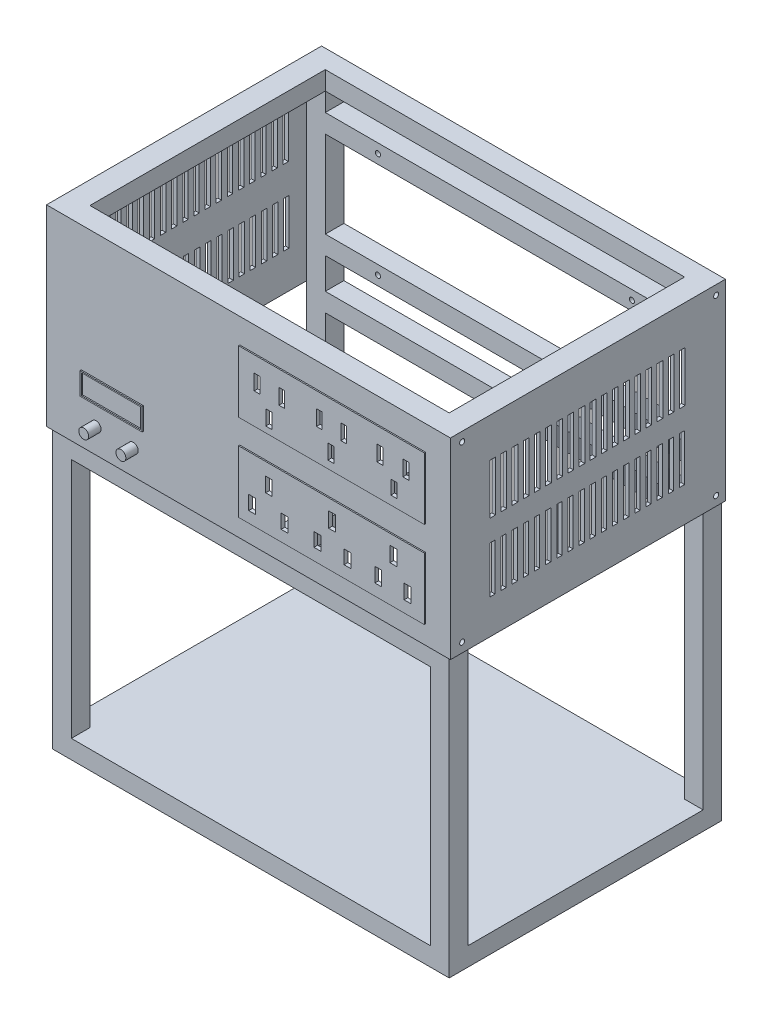
SolidWorks part; units mm, degrees
ref_plane "前视基准面" through (0, 0, 0) normal (0, 0, 1) x (1, 0, 0)
ref_plane "上视基准面" through (0, 0, 0) normal (0, 1, 0) x (1, 0, 0)
ref_plane "右视基准面" through (0, 0, 0) normal (1, 0, 0) x (0, 0, -1)
sketch "草图1" plane through (0, 0, 0) normal (0, 1, 0) x (1, 0, 0)
  line L1 (-160, 110) -> (160, 110)
  line L2 (-160, 110) -> (-160, -110)
  line L3 (-160, -110) -> (160, -110)
  line L4 (160, 110) -> (160, -110)
  line L5 (-160, 110) -> (160, -110) construction
  line L6 (-160, -110) -> (160, 110) construction
  point P0 (0, 0)
  dimension "D1" = 320
  dimension "D2" = 220
extrude "凸台-拉伸2" add sketch "草图1" along normal blind 380
sketch "草图3" plane through (0, 0, 110) normal (0, 0, 1) x (1, 0, 0)
  line L0 (-160, 380) -> (160, 380) construction
  line L1 (-145, 365) -> (145, 365)
  line L2 (-145, 365) -> (-145, 15)
  line L3 (-145, 15) -> (145, 15)
  line L4 (145, 365) -> (145, 15)
  line L5 (160, 380) -> (160, 0) construction
  dimension "D1" = 290
  dimension "D2" = 350
  dimension "D3" = 15
  dimension "D4" = 15
extrude "切除-拉伸1" cut sketch "草图3" against normal blind 220
sketch "草图4" plane through (160, 0, 0) normal (1, 0, 0) x (0, 0, -1)
  line L0 (-110, 380) -> (110, 380) construction
  line L1 (-95, 365) -> (95, 365)
  line L2 (-95, 365) -> (-95, 15)
  line L3 (-95, 15) -> (95, 15)
  line L4 (95, 365) -> (95, 15)
  line L5 (110, 380) -> (110, 0) construction
  dimension "D1" = 190
  dimension "D2" = 350
  dimension "D3" = 15
  dimension "D4" = 15
extrude "切除-拉伸2" cut sketch "草图4" against normal blind 320
sketch "草图5" plane through (0, 380, 0) normal (0, 1, 0) x (1, 0, 0)
  line L0 (160, 110) -> (-160, 110) construction
  line L1 (-145, 95) -> (145, 95)
  line L2 (-145, 95) -> (-145, -95)
  line L3 (-145, -95) -> (145, -95)
  line L4 (145, 95) -> (145, -95)
  line L5 (-160, 110) -> (-160, -110) construction
  dimension "D1" = 290
  dimension "D2" = 190
  dimension "D3" = 15
  dimension "D4" = 15
extrude "切除-拉伸3" cut sketch "草图5" against normal blind 15
sketch "草图6" plane through (0, 0, -110) normal (0, 0, -1) x (-1, 0, 0)
  line L0 (-145, 15) -> (-145, 365) construction
  line L1 (-145, 350) -> (145, 350)
  line L2 (-145, 350) -> (-145, 335)
  line L3 (-145, 335) -> (145, 335)
  line L4 (145, 350) -> (145, 335)
  line L5 (145, 365) -> (145, 15) construction
  line L6 (-145, 365) -> (145, 365) construction
  dimension "D1" = 15
  dimension "D2" = 15
extrude "凸台-拉伸3" add sketch "草图6" against normal blind 15
sketch "草图7" plane through (0, 0, -110) normal (0, 0, -1) x (-1, 0, 0)
  line L0 (-145, 15) -> (-145, 335) construction
  line L1 (-145, 265) -> (145, 265)
  line L2 (-145, 265) -> (-145, 250)
  line L3 (-145, 250) -> (145, 250)
  line L4 (145, 265) -> (145, 250)
  line L5 (145, 335) -> (145, 15) construction
  line L6 (145, 350) -> (-145, 350) construction
  dimension "D1" = 15
  dimension "D2" = 85
extrude "凸台-拉伸4" add sketch "草图7" against normal blind 15
sketch "草图8" plane through (0, 0, -110) normal (0, 0, -1) x (-1, 0, 0)
  line L0 (-160, 380) -> (-160, 0) construction
  line L1 (145, 350) -> (-145, 350) construction
  circle A0 centre (-102.5, 342.5) radius 2.05
  dimension "D1" = 4.1
  dimension "D2" = 57.5
  dimension "D3" = 7.5
extrude "切除-拉伸4" cut sketch "草图8" against normal blind 15
sketch "草图9" plane through (0, 0, -110) normal (0, 0, -1) x (-1, 0, 0)
  line L0 (160, 380) -> (160, 0) construction
  line L1 (145, 350) -> (-145, 350) construction
  circle A0 centre (102.5, 342.5) radius 2.05
  dimension "D1" = 4.1
  dimension "D2" = 57.5
  dimension "D3" = 7.5
extrude "切除-拉伸5" cut sketch "草图9" against normal blind 15
sketch "草图10" plane through (0, 0, -110) normal (0, 0, -1) x (-1, 0, 0)
  line L0 (145, 265) -> (-145, 265) construction
  line L1 (-160, 380) -> (-160, 0) construction
  circle A0 centre (-102.5, 257.5) radius 2.05
  dimension "D1" = 4.1
  dimension "D2" = 7.5
  dimension "D3" = 57.5
extrude "切除-拉伸6" cut sketch "草图10" against normal blind 15
sketch "草图11" plane through (0, 0, -110) normal (0, 0, -1) x (-1, 0, 0)
  line L0 (145, 265) -> (-145, 265) construction
  line L1 (160, 380) -> (160, 0) construction
  circle A0 centre (102.5, 257.5) radius 2.05
  dimension "D1" = 4.1
  dimension "D2" = 7.5
  dimension "D3" = 57.5
extrude "切除-拉伸7" cut sketch "草图11" against normal blind 15
sketch "草图12" plane through (0, 0, 110) normal (0, 0, 1) x (1, 0, 0)
  line L0 (-145, 365) -> (-145, 15) construction
  line L1 (-145, 225) -> (145, 225)
  line L2 (-145, 225) -> (-145, 210)
  line L3 (-145, 210) -> (145, 210)
  line L4 (145, 225) -> (145, 210)
  line L5 (145, 15) -> (145, 365) construction
  line L6 (-145, 15) -> (145, 15) construction
  dimension "D1" = 15
  dimension "D2" = 195
extrude "凸台-拉伸5" add sketch "草图12" against normal blind 15
sketch "草图13" plane through (0, 0, -110) normal (0, 0, -1) x (-1, 0, 0)
  line L0 (145, 210) -> (-145, 210) construction
  line L1 (-145, 225) -> (145, 225)
  line L2 (-145, 225) -> (-145, 210)
  line L3 (-145, 210) -> (145, 210)
  line L4 (145, 225) -> (145, 210)
  line L5 (145, 250) -> (145, 15) construction
extrude "凸台-拉伸6" add sketch "草图13" against normal blind 15
sketch "草图14" plane through (0, 0, -110) normal (0, 0, -1) x (-1, 0, 0)
  line L0 (145, 225) -> (-145, 225) construction
  line L1 (-15, 225) -> (0, 225)
  line L2 (-15, 225) -> (-15, 210)
  line L3 (-15, 210) -> (0, 210)
  line L4 (0, 225) -> (0, 210)
  line L5 (-145, 210) -> (145, 210) construction
  dimension "D1" = 15
extrude "凸台-拉伸7" add sketch "草图14" against normal blind 220
sketch "草图15" plane through (160, 0, 0) normal (1, 0, 0) x (0, 0, -1)
  line L0 (110, 380) -> (110, 0) construction
  line L1 (-110, 380) -> (110, 380)
  line L2 (-110, 380) -> (-110, 224.9999)
  line L3 (-110, 224.9999) -> (110, 224.9999)
  line L4 (110, 380) -> (110, 224.9999)
extrude "凸台-拉伸9" add sketch "草图15" along normal blind 3 contours L3 L4 L1 L2
sketch "草图17" plane through (163, 0, 0) normal (1, 0, 0) x (0, 0, -1)
  line L0 (-110, 380) -> (110, 380) construction
  line L1 (-110, 380) -> (-110, 224.9999) construction
  circle A0 centre (-102.5, 372.5) radius 2.05
  dimension "D1" = 4.1
  dimension "D2" = 7.5
  dimension "D3" = 7.5
extrude "切除-拉伸9" cut sketch "草图17" against normal blind 3
sketch "草图18" plane through (163, 0, 0) normal (1, 0, 0) x (0, 0, -1)
  line L0 (-110, 380) -> (110, 380) construction
  line L1 (110, 380) -> (110, 224.9999) construction
  circle A0 centre (102.5, 372.5) radius 2.05
  dimension "D1" = 4.1
  dimension "D2" = 7.5
  dimension "D3" = 7.5
extrude "切除-拉伸10" cut sketch "草图18" against normal blind 3
sketch "草图19" plane through (163, 0, 0) normal (1, 0, 0) x (0, 0, -1)
  line L0 (-110, 380) -> (-110, 224.9999) construction
  line L1 (-110, 224.9999) -> (-95, 224.9999) construction
  circle A0 centre (-102.5, 232.4999) radius 2.05
  dimension "D1" = 4.1
  dimension "D2" = 7.5
  dimension "D3" = 7.5
extrude "切除-拉伸11" cut sketch "草图19" against normal blind 3
sketch "草图20" plane through (163, 0, 0) normal (1, 0, 0) x (0, 0, -1)
  line L0 (-110, 224.9999) -> (110, 224.9999) construction
  line L1 (110, 380) -> (110, 224.9999) construction
  circle A0 centre (102.5, 232.4999) radius 2.05
  dimension "D1" = 4.1
  dimension "D2" = 7.5
  dimension "D3" = 7.5
extrude "切除-拉伸12" cut sketch "草图20" against normal blind 3
sketch "草图21" plane through (-160, 0, 0) normal (-1, 0, 0) x (0, 0, 1)
  line L0 (110, 380) -> (110, 0) construction
  line L1 (-110, 380) -> (110, 380)
  line L2 (-110, 380) -> (-110, 224.9399)
  line L3 (-110, 224.9399) -> (110, 224.9399)
  line L4 (110, 380) -> (110, 224.9399)
extrude "凸台-拉伸10" add sketch "草图21" along normal blind 3
sketch "草图22" plane through (-163, 0, 0) normal (-1, 0, 0) x (0, 0, 1)
  line L0 (110, 380) -> (-110, 380) construction
  line L1 (-110, 380) -> (-110, 224.9399) construction
  circle A0 centre (-102.5, 372.5) radius 2.05
  dimension "D1" = 4.1
  dimension "D2" = 7.5
  dimension "D3" = 7.5
extrude "切除-拉伸13" cut sketch "草图22" against normal blind 3
sketch "草图23" plane through (-163, 0, 0) normal (-1, 0, 0) x (0, 0, 1)
  line L0 (110, 380) -> (-110, 380) construction
  line L1 (110, 224.9399) -> (110, 380) construction
  circle A0 centre (102.5, 372.5) radius 2.05
  dimension "D1" = 4.1
  dimension "D2" = 7.5
  dimension "D3" = 7.5
extrude "切除-拉伸14" cut sketch "草图23" against normal blind 3
sketch "草图24" plane through (-163, 0, 0) normal (-1, 0, 0) x (0, 0, 1)
  line L0 (-110, 380) -> (-110, 224.9399) construction
  line L1 (-110, 224.9399) -> (110, 224.9399) construction
  circle A0 centre (-102.5, 232.4399) radius 2.05
  dimension "D1" = 4.1
  dimension "D2" = 7.5
  dimension "D3" = 7.5
extrude "切除-拉伸15" cut sketch "草图24" against normal blind 3
sketch "草图25" plane through (-163, 0, 0) normal (-1, 0, 0) x (0, 0, 1)
  line L0 (-110, 224.9399) -> (110, 224.9399) construction
  line L1 (110, 224.9399) -> (110, 380) construction
  circle A0 centre (102.5, 232.4399) radius 2.05
  dimension "D1" = 4.1
  dimension "D2" = 7.5
  dimension "D3" = 7.5
extrude "切除-拉伸16" cut sketch "草图25" against normal blind 3
sketch "草图26" plane through (0, 0, 110) normal (0, 0, 1) x (1, 0, 0)
  line L1 (-163, 380) -> (163, 380)
  line L2 (-163, 380) -> (-163, 224.9999)
  line L3 (-163, 224.9999) -> (163, 224.9999)
  line L4 (163, 380) -> (163, 224.9999)
extrude "凸台-拉伸11" add sketch "草图26" along normal blind 2
sketch "草图27" plane through (0, 0, 112) normal (0, 0, 1) x (1, 0, 0)
  line L0 (-163, 224.9999) -> (163, 224.9999) construction
  line L1 (-163, 380) -> (-163, 224.9999) construction
  circle A0 centre (-123, 244.9999) radius 4
  dimension "D1" = 8
  dimension "D2" = 20
  dimension "D3" = 40
extrude "凸台-拉伸12" add sketch "草图27" along normal blind 10
sketch "草图28" plane through (0, 0, 112) normal (0, 0, 1) x (1, 0, 0)
  line L0 (-163, 380) -> (-163, 224.9999) construction
  line L1 (-163, 224.9999) -> (160, 224.9999) construction
  circle A0 centre (-93, 244.9999) radius 4
  dimension "D1" = 8
  dimension "D2" = 70
  dimension "D3" = 20
extrude "凸台-拉伸13" add sketch "草图28" along normal blind 10
sketch "草图29" plane through (0, 0, 112) normal (0, 0, 1) x (1, 0, 0)
  line L1 (-134.9072, 278.6472) -> (-84.9072, 278.6472)
  line L2 (-134.9072, 278.6472) -> (-134.9072, 260.6472)
  line L3 (-134.9072, 260.6472) -> (-84.9072, 260.6472)
  line L4 (-84.9072, 278.6472) -> (-84.9072, 260.6472)
  dimension "D1" = 50
  dimension "D2" = 18
extrude "凸台-拉伸14" add sketch "草图29" along normal blind 1
sketch "草图30" plane through (0, 0, 113) normal (0, 0, 1) x (1, 0, 0)
  line L1 (-133.8607, 277.6694) -> (-85.9765, 277.6694)
  line L2 (-133.8607, 277.6694) -> (-133.8607, 261.6653)
  line L3 (-133.8607, 261.6653) -> (-85.9765, 261.6653)
  line L4 (-85.9765, 277.6694) -> (-85.9765, 261.6653)
extrude "切除-拉伸17" cut sketch "草图30" against normal blind 1
sketch "草图31" plane through (0, 0, 112) normal (0, 0, 1) x (1, 0, 0)
  line L0 (163, 224.9999) -> (163, 380) construction
  line L1 (-7, 360) -> (143, 360)
  line L2 (-7, 360) -> (-7, 310)
  line L3 (-7, 310) -> (143, 310)
  line L4 (143, 360) -> (143, 310)
  line L5 (163, 380) -> (-163, 380) construction
  line L7 (-7, 290) -> (143, 290)
  line L8 (-7, 290) -> (-7, 240)
  line L9 (-7, 240) -> (143, 240)
  line L10 (143, 290) -> (143, 240)
  dimension "D1" = 150
  dimension "D2" = 50
  dimension "D3" = 20
  dimension "D4" = 20
  dimension "D5" = 50
  dimension "D6" = 20
extrude "凸台-拉伸15" add sketch "草图31" along normal blind 1
sketch "草图33" plane through (0, 0, 113) normal (0, 0, 1) x (1, 0, 0)
  line L0 (43, 360) -> (43, 240) construction
  line L1 (143, 360) -> (-7, 360) construction
  line L2 (-7, 240) -> (143, 240) construction
  line L3 (-7, 360) -> (-7, 310) construction
  line L4 (93, 360) -> (93, 240) construction
  dimension "D1" = 50
  dimension "D2" = 50
sketch "草图35" plane through (0, 0, 113) normal (0, 0, 1) x (1, 0, 0)
  line L1 (5.6059, 347.1544) -> (10.1058, 347.1544)
  line L2 (5.6059, 347.1544) -> (5.6059, 334.6931)
  line L3 (5.6059, 334.6931) -> (10.1058, 334.6931)
  line L4 (10.1058, 347.1544) -> (10.1058, 334.6931)
  line L5 (25.5094, 347.1544) -> (30.0093, 347.1544)
  line L6 (25.5094, 347.1544) -> (25.5094, 334.6931)
  line L7 (25.5094, 334.6931) -> (30.0093, 334.6931)
  line L8 (30.0093, 347.1544) -> (30.0093, 334.6931)
  line L9 (14.9519, 326.9047) -> (19.971, 326.9047)
  line L10 (14.9519, 326.9047) -> (14.9519, 314.7896)
  line L11 (14.9519, 314.7896) -> (19.971, 314.7896)
  line L12 (19.971, 326.9047) -> (19.971, 314.7896)
extrude "切除-拉伸18" cut sketch "草图35" against normal blind 15
sketch "草图36" plane through (0, 0, 113) normal (0, 0, 1) x (1, 0, 0)
  line L1 (55.8581, 347.4272) -> (60.3497, 347.4272)
  line L2 (55.8581, 347.4272) -> (55.8581, 334.9505)
  line L3 (55.8581, 334.9505) -> (60.3497, 334.9505)
  line L4 (60.3497, 347.4272) -> (60.3497, 334.9505)
  line L5 (75.5713, 347.4272) -> (80.063, 347.4272)
  line L6 (75.5713, 347.4272) -> (75.5713, 334.9505)
  line L7 (75.5713, 334.9505) -> (80.063, 334.9505)
  line L8 (80.063, 347.4272) -> (80.063, 334.9505)
  line L9 (65.0909, 328.0883) -> (70.0816, 328.0883)
  line L10 (65.0909, 328.0883) -> (65.0909, 316.1107)
  line L11 (65.0909, 316.1107) -> (70.0816, 316.1107)
  line L12 (70.0816, 328.0883) -> (70.0816, 316.1107)
extrude "切除-拉伸19" cut sketch "草图36" against normal blind 15
sketch "草图37" plane through (0, 0, 113) normal (0, 0, 1) x (1, 0, 0)
  line L1 (104.6421, 347.1777) -> (109.508, 347.1777)
  line L2 (104.6421, 347.1777) -> (104.6421, 334.5762)
  line L3 (104.6421, 334.5762) -> (109.508, 334.5762)
  line L4 (109.508, 347.1777) -> (109.508, 334.5762)
  line L5 (125.603, 347.1777) -> (130.7185, 347.1777)
  line L6 (125.603, 347.1777) -> (125.603, 334.5762)
  line L7 (125.603, 334.5762) -> (130.7185, 334.5762)
  line L8 (130.7185, 347.1777) -> (130.7185, 334.5762)
  line L9 (115.8712, 328.2131) -> (120.7371, 328.2131)
  line L10 (115.8712, 328.2131) -> (115.8712, 316.984)
  line L11 (115.8712, 316.984) -> (120.7371, 316.984)
  line L12 (120.7371, 328.2131) -> (120.7371, 316.984)
extrude "切除-拉伸20" cut sketch "草图37" against normal blind 15
sketch "草图38" plane through (0, 0, 113) normal (0, 0, 1) x (1, 0, 0)
  line L1 (14.8093, 279.771) -> (20.0775, 279.771)
  line L2 (14.8093, 279.771) -> (14.8093, 268.0822)
  line L3 (14.8093, 268.0822) -> (20.0775, 268.0822)
  line L4 (20.0775, 279.771) -> (20.0775, 268.0822)
  line L5 (1.1449, 260.1798) -> (6.5777, 260.1798)
  line L6 (1.1449, 260.1798) -> (1.1449, 248.8202)
  line L7 (1.1449, 248.8202) -> (6.5777, 248.8202)
  line L8 (6.5777, 260.1798) -> (6.5777, 248.8202)
  line L9 (27.3213, 260.1798) -> (32.9188, 260.1798)
  line L10 (27.3213, 260.1798) -> (27.3213, 248.8202)
  line L11 (27.3213, 248.8202) -> (32.9188, 248.8202)
  line L12 (32.9188, 260.1798) -> (32.9188, 248.8202)
extrude "切除-拉伸21" cut sketch "草图38" against normal blind 15
sketch "草图39" plane through (0, 0, 113) normal (0, 0, 1) x (1, 0, 0)
  line L1 (65.6806, 280.9234) -> (71.1134, 280.9234)
  line L2 (65.6806, 280.9234) -> (65.6806, 268.7407)
  line L3 (65.6806, 268.7407) -> (71.1134, 268.7407)
  line L4 (71.1134, 280.9234) -> (71.1134, 268.7407)
  line L5 (53.8271, 260.5091) -> (59.4246, 260.5091)
  line L6 (53.8271, 260.5091) -> (53.8271, 249.4788)
  line L7 (53.8271, 249.4788) -> (59.4246, 249.4788)
  line L8 (59.4246, 260.5091) -> (59.4246, 249.4788)
  line L9 (78.1926, 260.5091) -> (83.6254, 260.5091)
  line L10 (78.1926, 260.5091) -> (78.1926, 249.4788)
  line L11 (78.1926, 249.4788) -> (83.6254, 249.4788)
  line L12 (83.6254, 260.5091) -> (83.6254, 249.4788)
extrude "切除-拉伸22" cut sketch "草图39" against normal blind 15
sketch "草图40" plane through (0, 0, 113) normal (0, 0, 1) x (1, 0, 0)
  line L1 (115.2348, 281.582) -> (120.8322, 281.582)
  line L2 (115.2348, 281.582) -> (115.2348, 269.3992)
  line L3 (115.2348, 269.3992) -> (120.8322, 269.3992)
  line L4 (120.8322, 281.582) -> (120.8322, 269.3992)
  line L5 (103.052, 260.8384) -> (108.3202, 260.8384)
  line L6 (103.052, 260.8384) -> (103.052, 249.1495)
  line L7 (103.052, 249.1495) -> (108.3202, 249.1495)
  line L8 (108.3202, 260.8384) -> (108.3202, 249.1495)
  line L9 (126.5944, 260.8384) -> (132.0272, 260.8384)
  line L10 (126.5944, 260.8384) -> (126.5944, 249.1495)
  line L11 (126.5944, 249.1495) -> (132.0272, 249.1495)
  line L12 (132.0272, 260.8384) -> (132.0272, 249.1495)
extrude "切除-拉伸23" cut sketch "草图40" against normal blind 15
sketch "草图41" plane through (-163, 0, 0) normal (-1, 0, 0) x (0, 0, 1)
  line L0 (-71.2312, 351.0938) -> (-71.2312, 315.602)
  line L1 (-80.2312, 351.0938) -> (-75.9573, 351.0938)
  line L2 (-80.2312, 351.0938) -> (-80.2312, 315.602)
  line L3 (-80.2312, 315.602) -> (-75.9573, 315.602)
  line L4 (-75.9573, 351.0938) -> (-75.9573, 315.602)
  line L5 (-71.2312, 351.0938) -> (-66.9573, 351.0938)
  line L6 (-66.9573, 351.0938) -> (-66.9573, 315.602)
  line L7 (-71.2312, 315.602) -> (-66.9573, 315.602)
  line L8 (-62.2312, 351.0938) -> (-62.2312, 315.602)
  line L9 (-62.2312, 351.0938) -> (-57.9573, 351.0938)
  line L10 (-57.9573, 351.0938) -> (-57.9573, 315.602)
  line L11 (-62.2312, 315.602) -> (-57.9573, 315.602)
  line L12 (-53.2312, 351.0938) -> (-53.2312, 315.602)
  line L13 (-53.2312, 351.0938) -> (-48.9573, 351.0938)
  line L14 (-48.9573, 351.0938) -> (-48.9573, 315.602)
  line L15 (-53.2312, 315.602) -> (-48.9573, 315.602)
  line L16 (-44.2312, 351.0938) -> (-44.2312, 315.602)
  line L17 (-44.2312, 351.0938) -> (-39.9573, 351.0938)
  line L18 (-39.9573, 351.0938) -> (-39.9573, 315.602)
  line L19 (-44.2312, 315.602) -> (-39.9573, 315.602)
  line L20 (-35.2312, 351.0938) -> (-35.2312, 315.602)
  line L21 (-35.2312, 351.0938) -> (-30.9573, 351.0938)
  line L22 (-30.9573, 351.0938) -> (-30.9573, 315.602)
  line L23 (-35.2312, 315.602) -> (-30.9573, 315.602)
  line L24 (-26.2312, 351.0938) -> (-26.2312, 315.602)
  line L25 (-26.2312, 351.0938) -> (-21.9573, 351.0938)
  line L26 (-21.9573, 351.0938) -> (-21.9573, 315.602)
  line L27 (-26.2312, 315.602) -> (-21.9573, 315.602)
  line L28 (-17.2312, 351.0938) -> (-17.2312, 315.602)
  line L29 (-17.2312, 351.0938) -> (-12.9573, 351.0938)
  line L30 (-12.9573, 351.0938) -> (-12.9573, 315.602)
  line L31 (-17.2312, 315.602) -> (-12.9573, 315.602)
  line L32 (-8.2312, 351.0938) -> (-8.2312, 315.602)
  line L33 (-8.2312, 351.0938) -> (-3.9573, 351.0938)
  line L34 (-3.9573, 351.0938) -> (-3.9573, 315.602)
  line L35 (-8.2312, 315.602) -> (-3.9573, 315.602)
  line L36 (0.7688, 351.0938) -> (0.7688, 315.602)
  line L37 (0.7688, 351.0938) -> (5.0427, 351.0938)
  line L38 (5.0427, 351.0938) -> (5.0427, 315.602)
  line L39 (0.7688, 315.602) -> (5.0427, 315.602)
  line L40 (9.7688, 351.0938) -> (9.7688, 315.602)
  line L41 (9.7688, 351.0938) -> (14.0427, 351.0938)
  line L42 (14.0427, 351.0938) -> (14.0427, 315.602)
  line L43 (9.7688, 315.602) -> (14.0427, 315.602)
  line L44 (18.7688, 351.0938) -> (18.7688, 315.602)
  line L45 (18.7688, 351.0938) -> (23.0427, 351.0938)
  line L46 (23.0427, 351.0938) -> (23.0427, 315.602)
  line L47 (18.7688, 315.602) -> (23.0427, 315.602)
  line L48 (27.7688, 351.0938) -> (27.7688, 315.602)
  line L49 (27.7688, 351.0938) -> (32.0427, 351.0938)
  line L50 (32.0427, 351.0938) -> (32.0427, 315.602)
  line L51 (27.7688, 315.602) -> (32.0427, 315.602)
  line L52 (36.7688, 351.0938) -> (36.7688, 315.602)
  line L53 (36.7688, 351.0938) -> (41.0427, 351.0938)
  line L54 (41.0427, 351.0938) -> (41.0427, 315.602)
  line L55 (36.7688, 315.602) -> (41.0427, 315.602)
  line L56 (45.7688, 351.0938) -> (45.7688, 315.602)
  line L57 (45.7688, 351.0938) -> (50.0427, 351.0938)
  line L58 (50.0427, 351.0938) -> (50.0427, 315.602)
  line L59 (45.7688, 315.602) -> (50.0427, 315.602)
  line L60 (54.7688, 351.0938) -> (54.7688, 315.602)
  line L61 (54.7688, 351.0938) -> (59.0427, 351.0938)
  line L62 (59.0427, 351.0938) -> (59.0427, 315.602)
  line L63 (54.7688, 315.602) -> (59.0427, 315.602)
  line L64 (63.7688, 351.0938) -> (63.7688, 315.602)
  line L65 (63.7688, 351.0938) -> (68.0427, 351.0938)
  line L66 (68.0427, 351.0938) -> (68.0427, 315.602)
  line L67 (63.7688, 315.602) -> (68.0427, 315.602)
  line L68 (72.7688, 351.0938) -> (72.7688, 315.602)
  line L69 (72.7688, 351.0938) -> (77.0427, 351.0938)
  line L70 (77.0427, 351.0938) -> (77.0427, 315.602)
  line L71 (72.7688, 315.602) -> (77.0427, 315.602)
  dimension "D1" = 18
extrude "切除-拉伸26" cut sketch "草图41" against normal blind 10
sketch "草图42" plane through (-163, 0, 0) normal (-1, 0, 0) x (0, 0, 1)
  line L0 (-71.7655, 291.682) -> (-71.7655, 254.8581)
  line L1 (-80.7655, 291.682) -> (-76.3864, 291.682)
  line L2 (-80.7655, 291.682) -> (-80.7655, 254.8581)
  line L3 (-80.7655, 254.8581) -> (-76.3864, 254.8581)
  line L4 (-76.3864, 291.682) -> (-76.3864, 254.8581)
  line L5 (-71.7655, 291.682) -> (-67.3864, 291.682)
  line L6 (-67.3864, 291.682) -> (-67.3864, 254.8581)
  line L7 (-71.7655, 254.8581) -> (-67.3864, 254.8581)
  line L8 (-62.7655, 291.682) -> (-62.7655, 254.8581)
  line L9 (-62.7655, 291.682) -> (-58.3864, 291.682)
  line L10 (-58.3864, 291.682) -> (-58.3864, 254.8581)
  line L11 (-62.7655, 254.8581) -> (-58.3864, 254.8581)
  line L12 (-53.7655, 291.682) -> (-53.7655, 254.8581)
  line L13 (-53.7655, 291.682) -> (-49.3864, 291.682)
  line L14 (-49.3864, 291.682) -> (-49.3864, 254.8581)
  line L15 (-53.7655, 254.8581) -> (-49.3864, 254.8581)
  line L16 (-44.7655, 291.682) -> (-44.7655, 254.8581)
  line L17 (-44.7655, 291.682) -> (-40.3864, 291.682)
  line L18 (-40.3864, 291.682) -> (-40.3864, 254.8581)
  line L19 (-44.7655, 254.8581) -> (-40.3864, 254.8581)
  line L20 (-35.7655, 291.682) -> (-35.7655, 254.8581)
  line L21 (-35.7655, 291.682) -> (-31.3864, 291.682)
  line L22 (-31.3864, 291.682) -> (-31.3864, 254.8581)
  line L23 (-35.7655, 254.8581) -> (-31.3864, 254.8581)
  line L24 (-26.7655, 291.682) -> (-26.7655, 254.8581)
  line L25 (-26.7655, 291.682) -> (-22.3864, 291.682)
  line L26 (-22.3864, 291.682) -> (-22.3864, 254.8581)
  line L27 (-26.7655, 254.8581) -> (-22.3864, 254.8581)
  line L28 (-17.7655, 291.682) -> (-17.7655, 254.8581)
  line L29 (-17.7655, 291.682) -> (-13.3864, 291.682)
  line L30 (-13.3864, 291.682) -> (-13.3864, 254.8581)
  line L31 (-17.7655, 254.8581) -> (-13.3864, 254.8581)
  line L32 (-8.7655, 291.682) -> (-8.7655, 254.8581)
  line L33 (-8.7655, 291.682) -> (-4.3864, 291.682)
  line L34 (-4.3864, 291.682) -> (-4.3864, 254.8581)
  line L35 (-8.7655, 254.8581) -> (-4.3864, 254.8581)
  line L36 (0.2345, 291.682) -> (0.2345, 254.8581)
  line L37 (0.2345, 291.682) -> (4.6136, 291.682)
  line L38 (4.6136, 291.682) -> (4.6136, 254.8581)
  line L39 (0.2345, 254.8581) -> (4.6136, 254.8581)
  line L40 (9.2345, 291.682) -> (9.2345, 254.8581)
  line L41 (9.2345, 291.682) -> (13.6136, 291.682)
  line L42 (13.6136, 291.682) -> (13.6136, 254.8581)
  line L43 (9.2345, 254.8581) -> (13.6136, 254.8581)
  line L44 (18.2345, 291.682) -> (18.2345, 254.8581)
  line L45 (18.2345, 291.682) -> (22.6136, 291.682)
  line L46 (22.6136, 291.682) -> (22.6136, 254.8581)
  line L47 (18.2345, 254.8581) -> (22.6136, 254.8581)
  line L48 (27.2345, 291.682) -> (27.2345, 254.8581)
  line L49 (27.2345, 291.682) -> (31.6136, 291.682)
  line L50 (31.6136, 291.682) -> (31.6136, 254.8581)
  line L51 (27.2345, 254.8581) -> (31.6136, 254.8581)
  line L52 (36.2345, 291.682) -> (36.2345, 254.8581)
  line L53 (36.2345, 291.682) -> (40.6136, 291.682)
  line L54 (40.6136, 291.682) -> (40.6136, 254.8581)
  line L55 (36.2345, 254.8581) -> (40.6136, 254.8581)
  line L56 (45.2345, 291.682) -> (45.2345, 254.8581)
  line L57 (45.2345, 291.682) -> (49.6136, 291.682)
  line L58 (49.6136, 291.682) -> (49.6136, 254.8581)
  line L59 (45.2345, 254.8581) -> (49.6136, 254.8581)
  line L60 (54.2345, 291.682) -> (54.2345, 254.8581)
  line L61 (54.2345, 291.682) -> (58.6136, 291.682)
  line L62 (58.6136, 291.682) -> (58.6136, 254.8581)
  line L63 (54.2345, 254.8581) -> (58.6136, 254.8581)
  line L64 (63.2345, 291.682) -> (63.2345, 254.8581)
  line L65 (63.2345, 291.682) -> (67.6136, 291.682)
  line L66 (67.6136, 291.682) -> (67.6136, 254.8581)
  line L67 (63.2345, 254.8581) -> (67.6136, 254.8581)
  line L68 (72.2345, 291.682) -> (72.2345, 254.8581)
  line L69 (72.2345, 291.682) -> (76.6136, 291.682)
  line L70 (76.6136, 291.682) -> (76.6136, 254.8581)
  line L71 (72.2345, 254.8581) -> (76.6136, 254.8581)
  dimension "D1" = 18
extrude "切除-拉伸27" cut sketch "草图42" against normal blind 10
sketch "草图43" plane through (163, 0, 0) normal (1, 0, 0) x (0, 0, -1)
  line L0 (-71.1715, 348.4677) -> (-71.1715, 307.951)
  line L1 (-80.1715, 348.4677) -> (-75.5556, 348.4677)
  line L2 (-80.1715, 348.4677) -> (-80.1715, 307.951)
  line L3 (-80.1715, 307.951) -> (-75.5556, 307.951)
  line L4 (-75.5556, 348.4677) -> (-75.5556, 307.951)
  line L5 (-71.1715, 348.4677) -> (-66.5556, 348.4677)
  line L6 (-66.5556, 348.4677) -> (-66.5556, 307.951)
  line L7 (-71.1715, 307.951) -> (-66.5556, 307.951)
  line L8 (-62.1715, 348.4677) -> (-62.1715, 307.951)
  line L9 (-62.1715, 348.4677) -> (-57.5556, 348.4677)
  line L10 (-57.5556, 348.4677) -> (-57.5556, 307.951)
  line L11 (-62.1715, 307.951) -> (-57.5556, 307.951)
  line L12 (-53.1715, 348.4677) -> (-53.1715, 307.951)
  line L13 (-53.1715, 348.4677) -> (-48.5556, 348.4677)
  line L14 (-48.5556, 348.4677) -> (-48.5556, 307.951)
  line L15 (-53.1715, 307.951) -> (-48.5556, 307.951)
  line L16 (-44.1715, 348.4677) -> (-44.1715, 307.951)
  line L17 (-44.1715, 348.4677) -> (-39.5556, 348.4677)
  line L18 (-39.5556, 348.4677) -> (-39.5556, 307.951)
  line L19 (-44.1715, 307.951) -> (-39.5556, 307.951)
  line L20 (-35.1715, 348.4677) -> (-35.1715, 307.951)
  line L21 (-35.1715, 348.4677) -> (-30.5556, 348.4677)
  line L22 (-30.5556, 348.4677) -> (-30.5556, 307.951)
  line L23 (-35.1715, 307.951) -> (-30.5556, 307.951)
  line L24 (-26.1715, 348.4677) -> (-26.1715, 307.951)
  line L25 (-26.1715, 348.4677) -> (-21.5556, 348.4677)
  line L26 (-21.5556, 348.4677) -> (-21.5556, 307.951)
  line L27 (-26.1715, 307.951) -> (-21.5556, 307.951)
  line L28 (-17.1715, 348.4677) -> (-17.1715, 307.951)
  line L29 (-17.1715, 348.4677) -> (-12.5556, 348.4677)
  line L30 (-12.5556, 348.4677) -> (-12.5556, 307.951)
  line L31 (-17.1715, 307.951) -> (-12.5556, 307.951)
  line L32 (-8.1715, 348.4677) -> (-8.1715, 307.951)
  line L33 (-8.1715, 348.4677) -> (-3.5556, 348.4677)
  line L34 (-3.5556, 348.4677) -> (-3.5556, 307.951)
  line L35 (-8.1715, 307.951) -> (-3.5556, 307.951)
  line L36 (0.8285, 348.4677) -> (0.8285, 307.951)
  line L37 (0.8285, 348.4677) -> (5.4444, 348.4677)
  line L38 (5.4444, 348.4677) -> (5.4444, 307.951)
  line L39 (0.8285, 307.951) -> (5.4444, 307.951)
  line L40 (9.8285, 348.4677) -> (9.8285, 307.951)
  line L41 (9.8285, 348.4677) -> (14.4444, 348.4677)
  line L42 (14.4444, 348.4677) -> (14.4444, 307.951)
  line L43 (9.8285, 307.951) -> (14.4444, 307.951)
  line L44 (18.8285, 348.4677) -> (18.8285, 307.951)
  line L45 (18.8285, 348.4677) -> (23.4444, 348.4677)
  line L46 (23.4444, 348.4677) -> (23.4444, 307.951)
  line L47 (18.8285, 307.951) -> (23.4444, 307.951)
  line L48 (27.8285, 348.4677) -> (27.8285, 307.951)
  line L49 (27.8285, 348.4677) -> (32.4444, 348.4677)
  line L50 (32.4444, 348.4677) -> (32.4444, 307.951)
  line L51 (27.8285, 307.951) -> (32.4444, 307.951)
  line L52 (36.8285, 348.4677) -> (36.8285, 307.951)
  line L53 (36.8285, 348.4677) -> (41.4444, 348.4677)
  line L54 (41.4444, 348.4677) -> (41.4444, 307.951)
  line L55 (36.8285, 307.951) -> (41.4444, 307.951)
  line L56 (45.8285, 348.4677) -> (45.8285, 307.951)
  line L57 (45.8285, 348.4677) -> (50.4444, 348.4677)
  line L58 (50.4444, 348.4677) -> (50.4444, 307.951)
  line L59 (45.8285, 307.951) -> (50.4444, 307.951)
  line L60 (54.8285, 348.4677) -> (54.8285, 307.951)
  line L61 (54.8285, 348.4677) -> (59.4444, 348.4677)
  line L62 (59.4444, 348.4677) -> (59.4444, 307.951)
  line L63 (54.8285, 307.951) -> (59.4444, 307.951)
  line L64 (63.8285, 348.4677) -> (63.8285, 307.951)
  line L65 (63.8285, 348.4677) -> (68.4444, 348.4677)
  line L66 (68.4444, 348.4677) -> (68.4444, 307.951)
  line L67 (63.8285, 307.951) -> (68.4444, 307.951)
  line L68 (72.8285, 348.4677) -> (72.8285, 307.951)
  line L69 (72.8285, 348.4677) -> (77.4444, 348.4677)
  line L70 (77.4444, 348.4677) -> (77.4444, 307.951)
  line L71 (72.8285, 307.951) -> (77.4444, 307.951)
  dimension "D1" = 18
extrude "切除-拉伸28" cut sketch "草图43" against normal blind 10
sketch "草图44" plane through (163, 0, 0) normal (1, 0, 0) x (0, 0, -1)
  line L0 (-71.1676, 290.6653) -> (-71.1676, 252.9045)
  line L1 (-80.1676, 290.6653) -> (-75.972, 290.6653)
  line L2 (-80.1676, 290.6653) -> (-80.1676, 252.9045)
  line L3 (-80.1676, 252.9045) -> (-75.972, 252.9045)
  line L4 (-75.972, 290.6653) -> (-75.972, 252.9045)
  line L5 (-71.1676, 290.6653) -> (-66.972, 290.6653)
  line L6 (-66.972, 290.6653) -> (-66.972, 252.9045)
  line L7 (-71.1676, 252.9045) -> (-66.972, 252.9045)
  line L8 (-62.1676, 290.6653) -> (-62.1676, 252.9045)
  line L9 (-62.1676, 290.6653) -> (-57.972, 290.6653)
  line L10 (-57.972, 290.6653) -> (-57.972, 252.9045)
  line L11 (-62.1676, 252.9045) -> (-57.972, 252.9045)
  line L12 (-53.1676, 290.6653) -> (-53.1676, 252.9045)
  line L13 (-53.1676, 290.6653) -> (-48.972, 290.6653)
  line L14 (-48.972, 290.6653) -> (-48.972, 252.9045)
  line L15 (-53.1676, 252.9045) -> (-48.972, 252.9045)
  line L16 (-44.1676, 290.6653) -> (-44.1676, 252.9045)
  line L17 (-44.1676, 290.6653) -> (-39.972, 290.6653)
  line L18 (-39.972, 290.6653) -> (-39.972, 252.9045)
  line L19 (-44.1676, 252.9045) -> (-39.972, 252.9045)
  line L20 (-35.1676, 290.6653) -> (-35.1676, 252.9045)
  line L21 (-35.1676, 290.6653) -> (-30.972, 290.6653)
  line L22 (-30.972, 290.6653) -> (-30.972, 252.9045)
  line L23 (-35.1676, 252.9045) -> (-30.972, 252.9045)
  line L24 (-26.1676, 290.6653) -> (-26.1676, 252.9045)
  line L25 (-26.1676, 290.6653) -> (-21.972, 290.6653)
  line L26 (-21.972, 290.6653) -> (-21.972, 252.9045)
  line L27 (-26.1676, 252.9045) -> (-21.972, 252.9045)
  line L28 (-17.1676, 290.6653) -> (-17.1676, 252.9045)
  line L29 (-17.1676, 290.6653) -> (-12.972, 290.6653)
  line L30 (-12.972, 290.6653) -> (-12.972, 252.9045)
  line L31 (-17.1676, 252.9045) -> (-12.972, 252.9045)
  line L32 (-8.1676, 290.6653) -> (-8.1676, 252.9045)
  line L33 (-8.1676, 290.6653) -> (-3.972, 290.6653)
  line L34 (-3.972, 290.6653) -> (-3.972, 252.9045)
  line L35 (-8.1676, 252.9045) -> (-3.972, 252.9045)
  line L36 (0.8324, 290.6653) -> (0.8324, 252.9045)
  line L37 (0.8324, 290.6653) -> (5.028, 290.6653)
  line L38 (5.028, 290.6653) -> (5.028, 252.9045)
  line L39 (0.8324, 252.9045) -> (5.028, 252.9045)
  line L40 (9.8324, 290.6653) -> (9.8324, 252.9045)
  line L41 (9.8324, 290.6653) -> (14.028, 290.6653)
  line L42 (14.028, 290.6653) -> (14.028, 252.9045)
  line L43 (9.8324, 252.9045) -> (14.028, 252.9045)
  line L44 (18.8324, 290.6653) -> (18.8324, 252.9045)
  line L45 (18.8324, 290.6653) -> (23.028, 290.6653)
  line L46 (23.028, 290.6653) -> (23.028, 252.9045)
  line L47 (18.8324, 252.9045) -> (23.028, 252.9045)
  line L48 (27.8324, 290.6653) -> (27.8324, 252.9045)
  line L49 (27.8324, 290.6653) -> (32.028, 290.6653)
  line L50 (32.028, 290.6653) -> (32.028, 252.9045)
  line L51 (27.8324, 252.9045) -> (32.028, 252.9045)
  line L52 (36.8324, 290.6653) -> (36.8324, 252.9045)
  line L53 (36.8324, 290.6653) -> (41.028, 290.6653)
  line L54 (41.028, 290.6653) -> (41.028, 252.9045)
  line L55 (36.8324, 252.9045) -> (41.028, 252.9045)
  line L56 (45.8324, 290.6653) -> (45.8324, 252.9045)
  line L57 (45.8324, 290.6653) -> (50.028, 290.6653)
  line L58 (50.028, 290.6653) -> (50.028, 252.9045)
  line L59 (45.8324, 252.9045) -> (50.028, 252.9045)
  line L60 (54.8324, 290.6653) -> (54.8324, 252.9045)
  line L61 (54.8324, 290.6653) -> (59.028, 290.6653)
  line L62 (59.028, 290.6653) -> (59.028, 252.9045)
  line L63 (54.8324, 252.9045) -> (59.028, 252.9045)
  line L64 (63.8324, 290.6653) -> (63.8324, 252.9045)
  line L65 (63.8324, 290.6653) -> (68.028, 290.6653)
  line L66 (68.028, 290.6653) -> (68.028, 252.9045)
  line L67 (63.8324, 252.9045) -> (68.028, 252.9045)
  line L68 (72.8324, 290.6653) -> (72.8324, 252.9045)
  line L69 (72.8324, 290.6653) -> (77.028, 290.6653)
  line L70 (77.028, 290.6653) -> (77.028, 252.9045)
  line L71 (72.8324, 252.9045) -> (77.028, 252.9045)
  dimension "D1" = 18
extrude "切除-拉伸29" cut sketch "草图44" against normal blind 10
